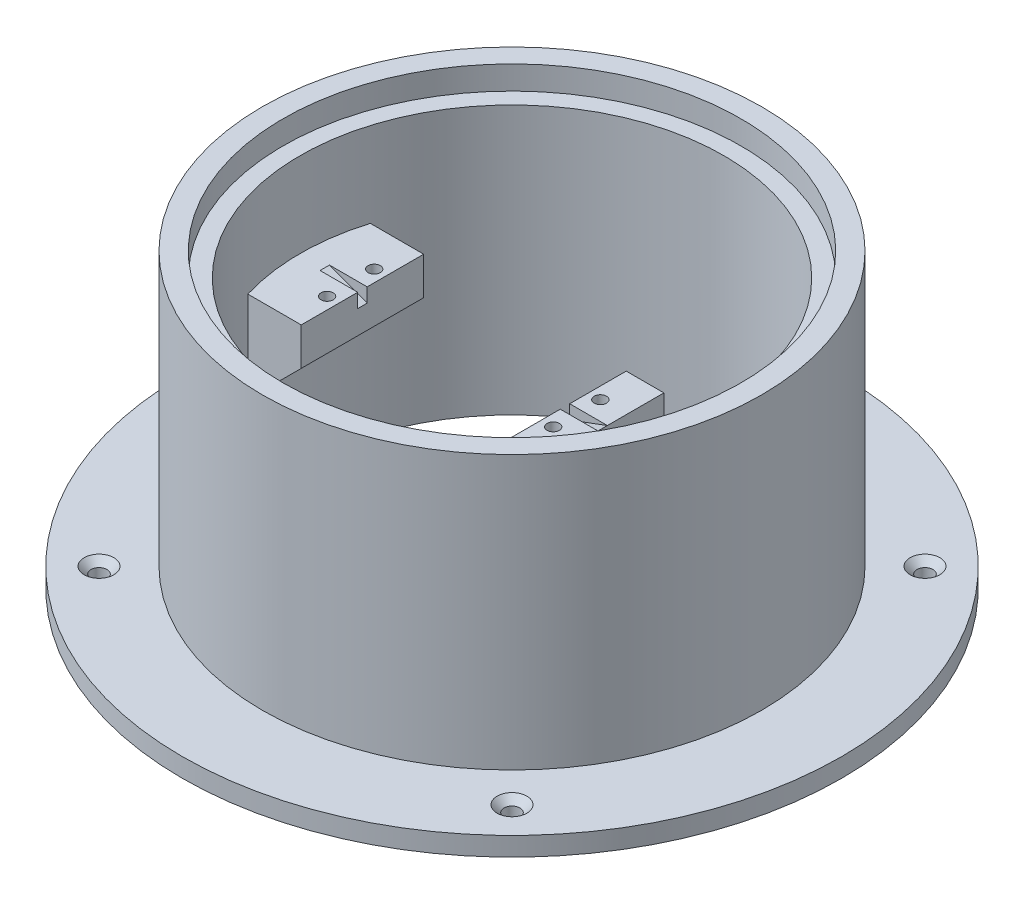
SolidWorks part; units mm, degrees
ref_plane "Front Plane" through (0, 0, 0) normal (0, 0, 1) x (1, 0, 0)
ref_plane "Top Plane" through (0, 0, 0) normal (0, 1, 0) x (1, 0, 0)
ref_plane "Right Plane" through (0, 0, 0) normal (1, 0, 0) x (0, 0, -1)
sketch "Sketch1" plane through (0, 0, 0) normal (0, 1, 0) x (1, 0, 0)
  circle A0 centre (0, 0) radius 70
  circle A1 centre (0, 0) radius 45
  dimension "D1" = 25
  dimension "D2" = 90
extrude "Boss-Extrude1" add sketch "Sketch1" along normal blind 4 contours A0
sketch "Sketch2" plane through (0, 4, 0) normal (0, 1, 0) x (1, 0, 0)
  circle A0 centre (0, 0) radius 45 construction
  circle A1 centre (0, 0) radius 45
  circle A2 centre (0, 0) radius 53
  dimension "D1" = 8
extrude "Boss-Extrude2" add sketch "Sketch2" along normal blind 53
ref_plane "Plane1" through (0, 37, 0) normal (0, 1, 0) x (1, 0, 0)
sketch "Sketch4" plane through (0, 0, 0) normal (0, 0, 1) x (1, 0, 0)
  line L0 (-70, 0) -> (70, 0) construction
  line L1 (11.25, 39) -> (19.25, 39)
  line L2 (11.25, 39) -> (11.25, 0)
  line L3 (11.25, 0) -> (19.25, 0)
  line L4 (19.25, 39) -> (19.25, 0)
  line L5 (53, 57) -> (-53, 57) construction
  line L6 (-45, 57) -> (-45, 4)
  line L7 (-31.75, 39) -> (-46.75, 39)
  line L8 (-31.75, 39) -> (-31.75, 31)
  line L9 (-31.75, 31) -> (-46.75, 31)
  line L10 (-46.75, 39) -> (-46.75, 31)
  line L11 (70, 4) -> (-70, 4) construction
  line L12 (-31.75, 31) -> (-45, 17.75)
  dimension "D1" = 11.25
  dimension "D2" = 8
  dimension "D3" = 18
  dimension "D4" = 43
  dimension "D5" = 15
  dimension "D6" = 8
  dimension "D7" = 45
  dimension "D8" = 18
extrude "Boss-Extrude4" add sketch "Sketch4" along normal mid plane 26 contours L9 L8 L7 L6 | L12 L9 L6 | L1 L4 L3 L2
sketch "Sketch5" plane through (0, 0, 0) normal (0, -1, 0) x (1, 0, 0)
  line L0 (11.25, 13) -> (29.0674, 34.3524)
  line L1 (11.25, -13) -> (29.0674, -34.3524)
  line L2 (11.25, 13) -> (11.25, -13)
  circle A0 centre (0, 0) radius 45 construction
  arc A1 (29.0674, -34.3524) -> (29.0674, 34.3524) centre (0, 0) ccw
extrude "Boss-Extrude5" add sketch "Sketch5" against normal up to surface (4 mm away) contours L0 A1 L1 L2 up to face at (0, 4, 70)
sketch "Sketch7" plane through (0, 39, 0) normal (0, 1, 0) x (1, 0, 0)
  line L0 (-31.75, -13) -> (-31.75, 13) construction
  circle A0 centre (-34.25, 5) radius 1.3
  circle A1 centre (-34.25, -5) radius 1.3
  circle A2 centre (13.75, 5) radius 1.3
  circle A3 centre (13.75, -5) radius 1.3
  dimension "D1" = 2.6
  dimension "D2" = 2.6
  dimension "D3" = 10
  dimension "D4" = 5
  dimension "D5" = 2.5
  dimension "D7" = 48
  dimension "D6" = 2
extrude "Cut-Extrude4" cut sketch "Sketch7" against normal blind 7.2
sketch "Sketch9" plane through (11.25, 0, 0) normal (-1, 0, 0) x (0, 0, 1)
  line L0 (13, 0) -> (-13, 0) construction
  line L1 (-5, 30) -> (5, 30)
  line L2 (-5, 30) -> (-5, 0)
  line L3 (-5, 0) -> (5, 0)
  line L4 (5, 30) -> (5, 0)
  line L5 (-5, 30) -> (5, 0) construction
  line L6 (-5, 0) -> (5, 30) construction
  line L7 (0, 0) -> (0, 30) construction
  line L8 (13, 39) -> (-13, 39) construction
  line L10 (5, 5) -> (-5, 5)
  point P0 (0, 15)
  dimension "D1" = 10
  dimension "D2" = 9
  dimension "D3" = 5
extrude "Cut-Extrude7" cut sketch "Sketch9" against normal up to surface (8 mm away) contours L10 L4 L1 L2 up to face at (19.25, 21.5, 0)
sketch "Sketch12" plane through (0, 4, 0) normal (0, 1, 0) x (1, 0, 0)
  line L5 (27.25, 19.6878) -> (27.25, -19.6878)
  line L6 (27.25, 19.6878) -> (27.25, -19.6878)
  line L9 (24.25, 16.0926) -> (24.25, -16.0926)
  line L10 (19.25, -13) -> (19.25, 13) construction
  line L18 (27.25, -19.6878) -> (29.4795, -22.3597)
  line L19 (29.4795, 22.3597) -> (27.25, 19.6878)
  line L21 (24.25, -16.0926) -> (29.4795, -22.3597)
  line L22 (29.4795, 22.3597) -> (24.25, 16.0926)
  arc A2 (29.4795, -22.3597) -> (29.4795, 22.3597) centre (0, 0) ccw
  arc A3 (29.4795, -22.3597) -> (29.4795, 22.3597) centre (0, 0) ccw
  dimension "D2" = 5
  dimension "D1" = 8
extrude "Cut-Extrude9" cut sketch "Sketch12" against normal through all contours L21 A3 L22 L6 | L6 L22 L9 L21
sketch "Sketch14" plane through (0, 4, 0) normal (0, 1, 0) x (1, 0, 0)
  line L0 (0, 0) -> (-43.8406, 43.8406) construction
  line L1 (11.25, 13) -> (19.25, 13) construction
  circle A0 centre (-43.8406, 43.8406) radius 1.5
  circle A1 centre (43.8406, 43.8406) radius 1.5
  circle A2 centre (43.8406, -43.8406) radius 1.5
  circle A3 centre (-43.8406, -43.8406) radius 1.5
  point P15 (0, 0)
  dimension "D1" = 3
  dimension "D2" = 62
  dimension "D3" = 135
  dimension "D4" = 4
hole_wizard "CSK for M3 Countersunk Flat Head Screw1" positions "Sketch15" profile "Sketch17" countersink size "M3" standard "DIN" end condition up to next
sketch "Sketch15" plane through (0, 4, 0) normal (0, 1, 0) x (1, 0, 0)
  point P0 (-43.8406, 43.8406)
  point P3 (-43.8406, -43.8406)
  point P6 (43.8406, -43.8406)
  point P9 (43.8406, 43.8406)
  point P12 (-38.8909, -38.8909)
sketch "Sketch17" plane through (-43.8406, 4, -43.8406) normal (1, 0, 0) x (0, 0, 1)
  line L0 (0, 0) -> (0, 4)
  line L1 (0, 4) -> (1.7, 4)
  line L2 (1.7, 4) -> (1.7, 1.45)
  line L3 (1.7, 1.45) -> (3.15, 0)
  line L5 (3.15, 0) -> (0, 0)
  line L6 (-1.7, 1.45) -> (-3.15, 0) construction
  line L11 (0, -6.35) -> (0, 107.95) construction
  dimension "Thru Hole Dia." = 3.4
  dimension "Thru Hole Depth" = 4
  dimension "Near C'Sink Dia." = 6.3
  dimension "Near C'Sink Angle" = 90
sketch "Sketch18" plane through (0, 57, 0) normal (0, 1, 0) x (1, 0, 0)
  circle A0 centre (0, 0) radius 48.6
  circle A1 centre (0, 0) radius 53
  circle A2 centre (0, 0) radius 53
  dimension "D2" = 97.2
  dimension "D1" = 0
extrude "Boss-Extrude6" add sketch "Sketch18" along normal blind 5
sketch "Sketch19" plane through (0, 0, 0) normal (0, 0, 1) x (1, 0, 0)
  line L0 (19.25, 4) -> (11.25, 4) construction
  line L1 (11.25, 4) -> (11.25, 39) construction
  line L2 (11.25, 39) -> (19.25, 39) construction
  line L3 (19.25, 39) -> (19.25, 4) construction
  line L4 (-43.0813, 19.6687) -> (-43.0813, 39) construction
  line L5 (-43.0813, 39) -> (-31.75, 39) construction
  line L6 (-31.75, 39) -> (-31.75, 31) construction
  line L7 (-31.75, 31) -> (-43.0813, 19.6687) construction
  line L8 (19.25, 4) -> (11.25, 4)
  line L9 (11.25, 4) -> (11.25, 39)
  line L10 (11.25, 39) -> (19.25, 39)
  line L11 (19.25, 39) -> (19.25, 4)
  line L12 (-43.0813, 19.6687) -> (-43.0813, 39)
  line L13 (-43.0813, 39) -> (-31.75, 39)
  line L14 (-31.75, 39) -> (-31.75, 31)
  line L15 (-31.75, 31) -> (-43.0813, 19.6687)
  line L16 (-39.75, 39) -> (-31.75, 36)
  line L17 (-31.75, 36) -> (-31.75, 39)
  line L18 (-39.75, 39) -> (-31.75, 39)
  line L19 (11.25, 39) -> (19.25, 39)
  line L20 (19.25, 39) -> (11.25, 36)
  line L21 (11.25, 36) -> (11.25, 39)
  dimension "D1" = 8
  dimension "D2" = 8
  dimension "D3" = 3
  dimension "D4" = 3
extrude "Cut-Extrude10" cut sketch "Sketch19" against normal mid plane 2 contours L18 L16 L17 | L19 L20 L21
